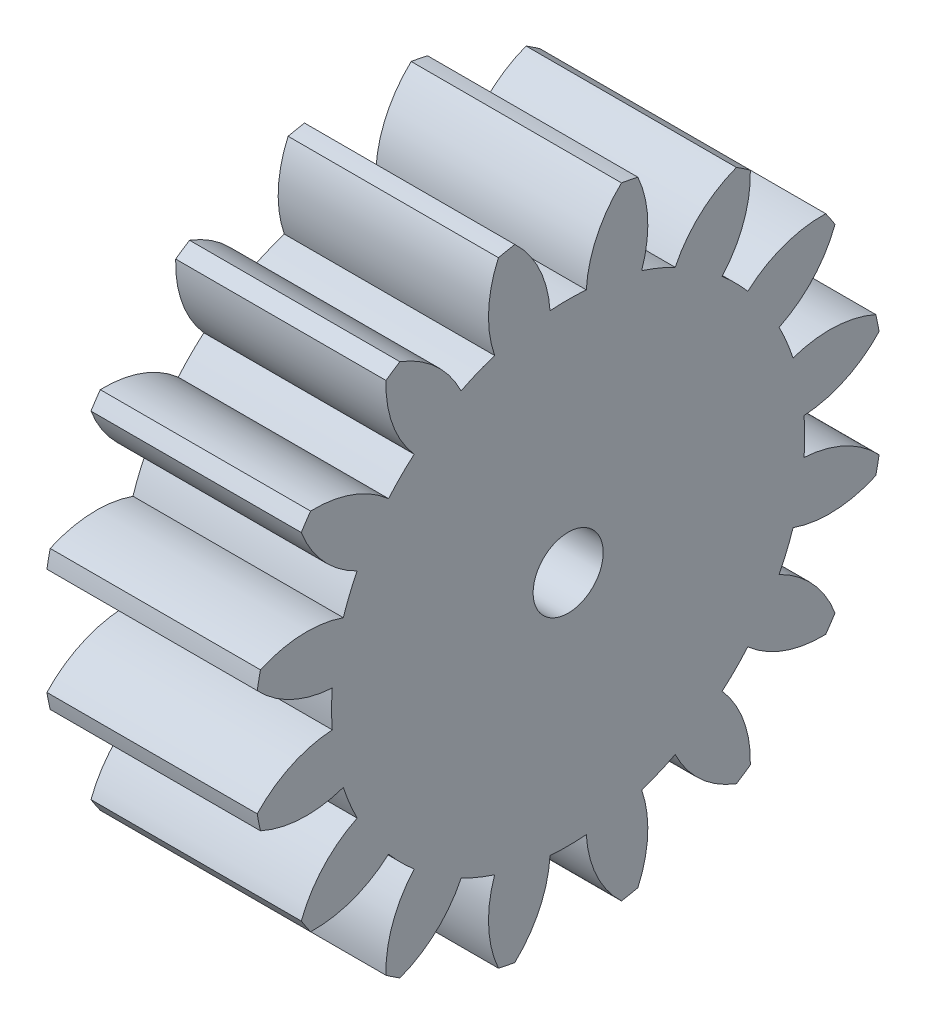
SolidWorks part; units mm, degrees
ref_plane "Plane1" through (0, 0, 0) normal (0, 0, 1) x (1, 0, 0)
ref_plane "Plane2" through (0, 0, 0) normal (0, 1, 0) x (1, 0, 0)
ref_plane "Plane3" through (0, 0, 0) normal (1, 0, 0) x (0, 0, -1)
sketch "HoldingSke" plane through (0, 0, 0) normal (0, 1, 0) x (1, 0, 0)
  line L0 (0, 0) -> (0.4806, -0.1378)
  line L1 (-15, 0) -> (100, 0) construction
  line L2 (0, 0) -> (-2.1039, 2.3779)
  line L3 (0, 0) -> (-11.863, 4.5341)
  line L4 (0, 0) -> (8.3015, 2.3804)
  line L5 (0, 0) -> (-46.8476, -17.4728)
  line L6 (0, 0) -> (-9.9476, -6.7116)
  line L7 (-2.1039, 2.3779) -> (8.6586, 51.2059)
  line L8 (-76.2, 54.61) -> (-75.5, 54.61)
  line L9 (-71.009, 38.7566) -> (-53.1078, 45.2721)
  line L10 (-76.2, 71.12) -> (104.1128, 71.12)
  line L11 (0, 0) -> (-12, 0)
  line L12 (-76.2, 101.6) -> (-76.133, 101.6)
  line L13 (24.9733, 27.94) -> (52.9518, 28.4284)
  line L14 (24.9733, 27.94) -> (24.9743, 27.94)
  line L15 (24.9733, 27.94) -> (100.4006, 29.5858)
  line L16 (-63.627, -2) -> (-12.827, -2)
  circle A0 centre (0, 0) radius 2
  circle A1 centre (0, 0) radius 13.499
  circle A2 centre (0, 0) radius 37.5
  circle A3 centre (0, 0) radius 2
  dimension "MHD" = 26.998
  dimension "Hub_dia" = 75
  dimension "Bore" = 4
  dimension "MBD" = 4
  dimension "Num_teeth" = 16
  dimension "Pitch_radius" = 180.3128
  dimension "Pitch" = 0.5
  dimension "Width" = 12
  dimension "Overall_len" = 50
  dimension "Show_teeth" = 16
  dimension "Thickness" = 12
  dimension "OAL" = 50.0001
  dimension "T_dim" = 0.7
  dimension "Ap" = 20
  dimension "H" = 19.05
  dimension "Backlash" = 0.067
  dimension "Addendum_fac" = 1
  dimension "Dedendum_fac" = 1.25
  dimension "Clearance_fac" = 0.25
  dimension "Dedendum_add" = 0.001
  dimension "Module" = 2
sketch "BasProSke" plane through (0, 0, 0) normal (0, 1, 0) x (1, 0, 0)
  line L0 (-10, 0) -> (60, 0) construction
  line L1 (0, 0) -> (0, 18)
  line L2 (0, 0) -> (12, 0)
  line L3 (12, 0) -> (12, 18)
  line L4 (12, 18) -> (0, 18)
  dimension "Diameter" = 36
  dimension "Thickness" = 12
revolve "Base-Revolve" add sketch "BasProSke" angle 360 about L0
sketch "TooCutSke" plane through (0, 0, 0) normal (1, 0, 0) x (0, 0, -1)
  line L1 (0, 0) -> (0, 107) construction
  line L2 (0, 0) -> (-1.6854, 15.911) construction
  line L3 (0, 0) -> (-6.2172, 31.2558) construction
  line L4 (-1.6854, 15.911) -> (-3.1086, 15.6279) construction
  arc A0 (1.0343, 13.4593) -> (-1.0343, 13.4593) centre (0, 0) ccw
  arc A1 (3.0657, 17.7628) -> (-3.0657, 17.7628) centre (0, 0) ccw
  circle A2 centre (0, 0) radius 16 construction
  circle A3 centre (0, 0) radius 15.0351 construction
  arc A4 (-1.0343, 13.4593) -> (-3.0657, 17.7628) centre (-7.4228, 13.075) ccw
  arc A5 (3.0657, 17.7628) -> (1.0343, 13.4593) centre (7.4228, 13.075) ccw
  dimension "Root_dia" = 26.998
  dimension "Overcut_dia" = 36.0508
  dimension "Pitch_dia" = 32
  dimension "Base_dia" = 30.0702
  dimension "Flank_rad" = 6.4
  dimension "Half_ang" = 11.25
  dimension "Half_CT" = 1.451
extrude "ToothCut" cut sketch "TooCutSke" along normal through all
fillet "Breaks" [suppressed] radius 0.04
fillet "RootFillets" [suppressed] radius 0.501
pattern_circular "TeethCuts" count 16 every 22.5 about axis through (-10, 0, 0) along (1, 0, 0) of "ToothCut", "RootFillets", "Breaks"
sketch "HubNeaOneSke" plane through (0, 0, 0) normal (-1, 0, 0) x (0, 0, 1)
  circle A0 centre (0, 0) radius 13.499
  dimension "Diameter" = 26.998
extrude "HubNearOne" [suppressed] add sketch "HubNeaOneSke" along normal blind 38.0001
sketch "HubNeaBotSke" plane through (0, 0, 0) normal (-1, 0, 0) x (0, 0, 1)
  circle A0 centre (0, 0) radius 13.499
  dimension "Diameter" = 26.998
extrude "HubNearBoth" [suppressed] add sketch "HubNeaBotSke" along normal blind 19
ref_plane "FarPln" through (12, 0, 0) normal (1, 0, 0) x (0, 0, -1)
sketch "HubFarSke" plane through (12, 0, 0) normal (1, 0, 0) x (0, 0, -1)
  circle A0 centre (0, 0) radius 13.499
  dimension "Diameter" = 26.998
extrude "HubFar" [suppressed] add sketch "HubFarSke" along normal blind 19
sketch "BorSke" plane through (0, 0, 0) normal (1, 0, 0) x (0, 0, -1)
  circle A0 centre (0, 0) radius 2
  dimension "Diameter" = 4
extrude "Bore" cut sketch "BorSke" along normal mid plane 100.0001
sketch "KeySke" plane through (0, 0, 0) normal (1, 0, 0) x (0, 0, -1)
  line L0 (-0.8, 0) -> (-0.8, 2.7)
  line L1 (-0.8, 2.7) -> (0.8, 2.7)
  line L2 (0.8, 2.7) -> (0.8, 0)
  line L3 (0, 0) -> (0, 34) construction
  line L4 (-0.8, 0) -> (0.8, 0)
  dimension "Offset" = 2.7
  dimension "Width" = 1.6
extrude "Keyway" [suppressed] cut sketch "KeySke" along normal mid plane 100.0001
pattern_circular "Keyway2" [suppressed] count 2 every 90 about axis through (-10, 0, 0) along (1, 0, 0)
equation "' \"Module@HoldingSke\" = 6.35"
equation "' \"Num_teeth@HoldingSke\" = 12"
equation "' \"Ap@HoldingSke\" =  20"
equation "' \"Width@HoldingSke\" = 0.5 * 25.4"
equation "' \"Hub_dia@HoldingSke\"= 1 * 25.4"
equation "' \"Overall_len@HoldingSke\" = 1.0 * 25.4"
equation "' \"Bore@HoldingSke\" = 0.75 * 25.4"
equation "' \"T_dim@HoldingSke\" = 0.1 * 25.4"
equation "' \"Width@KeySke\" = 0.25 * 25.4"
equation "' \"Show_teeth@HoldingSke\" = 13"
equation "' \"Backlash@HoldingSke\" = 0.009 * 25.4"
equation "' \"Addendum_fac@HoldingSke\" = 1.0"
equation "' \"Dedendum_fac@HoldingSke\" = 1.25"
equation "' \"Dedendum_add@HoldingSke\" = 0.00005 * 25.4"
equation "' \"Clearance_fac@HoldingSke\" = 0.25"
equation "\"Pitch@HoldingSke\" = 1 / \"Module@HoldingSke\""
equation "\"Overcut_dia@TooCutSke\" = (\"Num_teeth@HoldingSke\" + 2 * \"Addendum_fac@HoldingSke\") / \"Pitch@HoldingSke\" + 0.002 * 25.4"
equation "\"Pitch_dia@TooCutSke\" = \"Num_teeth@HoldingSke\" / \"Pitch@HoldingSke\""
equation "\"Base_dia@TooCutSke\" = \"Num_teeth@HoldingSke\" / \"Pitch@HoldingSke\" * cos((\"Ap@HoldingSke\"  * 3.14159265 / 180))"
equation "\"Root_dia@TooCutSke\" = (\"Num_teeth@HoldingSke\" + 2) / \"Pitch@HoldingSke\" - 2 * (\"Addendum_fac@HoldingSke\" + \"Dedendum_fac@HoldingSke\") / \"Pitch@HoldingSke\" - \"Dedendum_add@HoldingSke\" * 2"
equation "\"Half_ang@TooCutSke\" = 180 / \"Num_teeth@HoldingSke\""
equation "\"Half_CT@TooCutSke\" = \"Num_teeth@HoldingSke\" / \"Pitch@HoldingSke\" * sin((3.14159265 / 2 / \"Num_teeth@HoldingSke\")) / 2 - 7 * \"Backlash@HoldingSke\" / 4"
equation "\"Flank_rad@TooCutSke\" = \"Num_teeth@HoldingSke\" / \"Pitch@HoldingSke\" / 5"
equation "\"Radius@RootFillets\" = \"Clearance_fac@HoldingSke\" / \"Pitch@HoldingSke\" + \"Dedendum_add@HoldingSke\""
equation "\"Break_rad@Breaks\" = 0.02 / \"Pitch@HoldingSke\""
equation "\"Thickness@HoldingSke\" = \"Width@HoldingSke\""
equation "\"OAL@HoldingSke\" = \"Thickness@HoldingSke\""
equation "\"MHD@HoldingSke\" = (\"Num_teeth@HoldingSke\" + 2) / \"Pitch@HoldingSke\" - 2 * (\"Addendum_fac@HoldingSke\" + \"Dedendum_fac@HoldingSke\")  / \"Pitch@HoldingSke\" - \"Dedendum_add@HoldingSke\" * 2"
equation "\"MBD@HoldingSke\" = (\"Num_teeth@HoldingSke\" + 2) / \"Pitch@HoldingSke\" - 2 * (\"Addendum_fac@HoldingSke\" + \"Dedendum_fac@HoldingSke\")  / \"Pitch@HoldingSke\" - \"Dedendum_add@HoldingSke\" * 2 - 0.002 * 25.4"
equation "\"MHD@HoldingSke\" = ((sgn( \"MHD@HoldingSke\" - \"Hub_dia@HoldingSke\" )-1)*( \"MHD@HoldingSke\" - \"Hub_dia@HoldingSke\" ))/-2+ \"Hub_dia@HoldingSke\""
equation "\"MBD@HoldingSke\" = ((sgn( \"MBD@HoldingSke\" - \"Bore@HoldingSke\" )-1)*( \"MBD@HoldingSke\" - \"Bore@HoldingSke\" ))/-2+ \"Bore@HoldingSke\""
equation "\"OAL@HoldingSke\" = ((sgn( \"OAL@HoldingSke\" - \"Overall_len@HoldingSke\" )+1)*( \"OAL@HoldingSke\" - \"Overall_len@HoldingSke\" ))/2 + \"Overall_len@HoldingSke\" + 0.000002 * 25.4"
equation "\"Num_teeth@TeethCuts\" = int( \"Show_teeth@HoldingSke\" ) + 1"
equation "\"Num_teeth@TeethCuts\" = ((sgn( \"Num_teeth@TeethCuts\" - \"Num_teeth@HoldingSke\" )-1)*( \"Num_teeth@TeethCuts\" - \"Num_teeth@HoldingSke\" ))/-2+ \"Num_teeth@HoldingSke\""
equation "\"Num_teeth@TeethCuts\" = ((sgn( \"Num_teeth@TeethCuts\" - 2.0)+1)*( \"Num_teeth@TeethCuts\" - 2.0))/2 +2.0"
equation "\"Angle@TeethCuts\" = 360.0 / \"Num_teeth@HoldingSke\""
equation "\"Diameter@BasProSke\" = (\"Num_teeth@HoldingSke\" + 2 * \"Addendum_fac@HoldingSke\") / \"Pitch@HoldingSke\""
equation "\"Thickness@BasProSke\"  = \"Thickness@HoldingSke\""
equation "' \"Fillet_rad@BasProSke\" =  \"Thickness@HoldingSke\" * 0.05"
equation "\"MHD@HoldingSke\" = ((sgn( \"MHD@HoldingSke\" - \"Root_dia@TooCutSke\" )-1)*( \"MHD@HoldingSke\" - \"Root_dia@TooCutSke\" ))/-2+ \"Root_dia@TooCutSke\""
equation "\"Diameter@HubNeaOneSke\" = \"MHD@HoldingSke\""
equation "\"Length@HubNearOne\" = \"OAL@HoldingSke\" - \"Thickness@BasProSke\""
equation "\"Diameter@HubNeaBotSke\" = \"MHD@HoldingSke\""
equation "\"Length@HubNearBoth\" = ( \"OAL@HoldingSke\" - \"Thickness@BasProSke\" ) / 2.0"
equation "\"Thickness@FarPln\" = \"Thickness@BasProSke\""
equation "\"Diameter@HubFarSke\" = \"MHD@HoldingSke\""
equation "\"Length@HubFar\" = ( \"OAL@HoldingSke\" - \"Thickness@BasProSke\" ) / 2.0"
equation "\"Diameter@BorSke\" = \"MBD@HoldingSke\""
equation "\"D1@Bore\" = \"OAL@HoldingSke\" * 2.0"
equation "\"D1@Keyway\" = \"OAL@HoldingSke\" * 2.0"
equation "\"Offset@KeySke\" = \"T_dim@HoldingSke\" + \"MBD@HoldingSke\" / 2.0"
